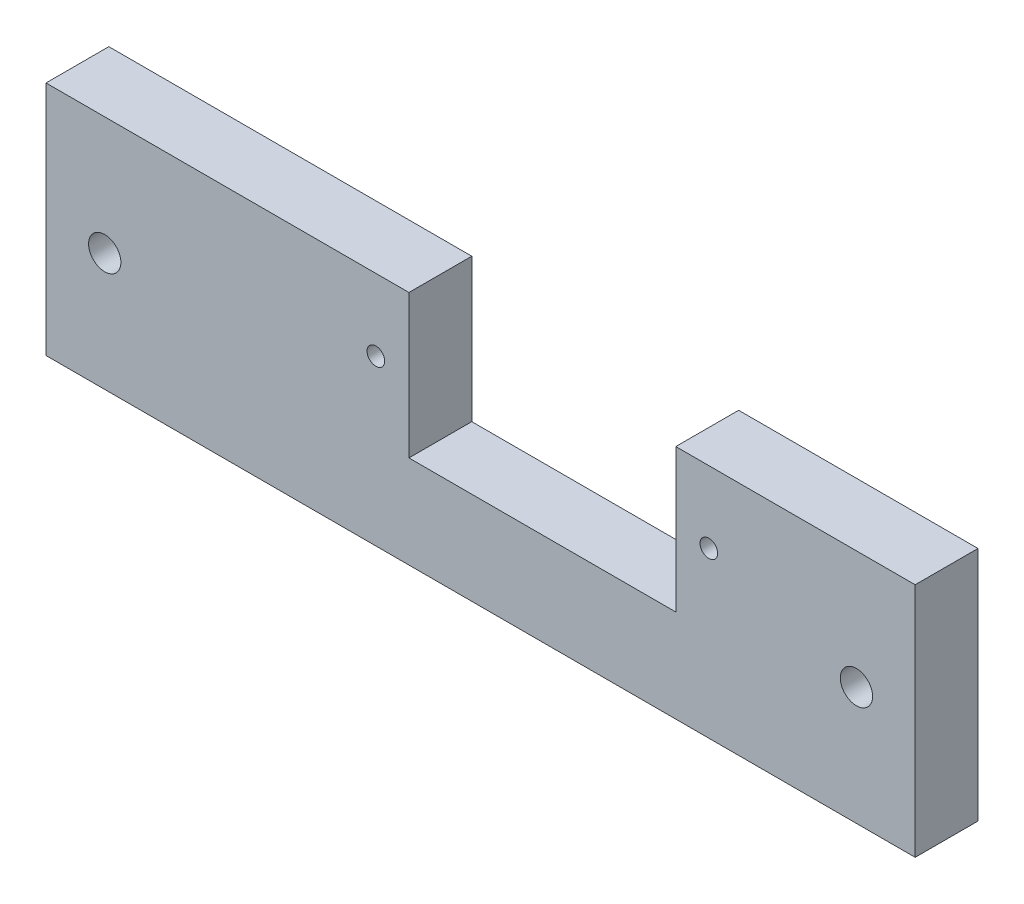
SolidWorks part; units mm, degrees
ref_plane "Front Plane" through (0, 0, 0) normal (0, 0, 1) x (1, 0, 0)
ref_plane "Top Plane" through (0, 0, 0) normal (0, 1, 0) x (1, 0, 0)
ref_plane "Right Plane" through (0, 0, 0) normal (1, 0, 0) x (0, 0, -1)
sketch "Model" plane through (0, 0, 0) normal (0, 0, 1) x (1, 0, 0)
  line L380 (30.9, 20.1) -> (30.9, 7.9)
  line L381 (30.9, 7.9) -> (53.62, 7.9)
  line L382 (53.62, 7.9) -> (53.62, 20.1)
  line L383 (74, 0) -> (0, 0)
  line L384 (74, 20.1) -> (74, 0)
  line L385 (0, 20.1) -> (30.9, 20.1)
  line L386 (0, 0) -> (0, 20.1)
  line L387 (53.62, 20.1) -> (74, 20.1)
  circle A40 centre (69, 10.05) radius 1.375
  circle A41 centre (5, 10.05) radius 1.375
  circle A42 centre (56.4337, 14) radius 0.75
  circle A43 centre (28.0863, 14) radius 0.75
  circle A44 centre (5, 10.05) radius 1.2
  circle A45 centre (69, 10.05) radius 1.2
extrude "Boss-Extrude1" add sketch "Model" along normal blind 5.35 contours L387 L382 L381 L380 L385 L386 L383 L384 A43 A42 A41 A40
